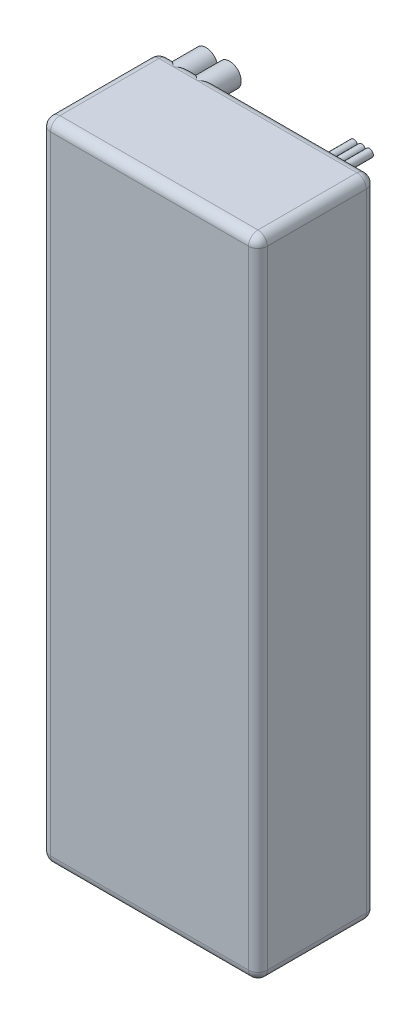
SolidWorks part; units mm, degrees
material "Rubber"
ref_plane "Front" through (0, 0, 0) normal (0, 0, 1) x (1, 0, 0)
ref_plane "Top" through (0, 0, 0) normal (0, 1, 0) x (1, 0, 0)
ref_plane "Right" through (0, 0, 0) normal (1, 0, 0) x (0, 0, -1)
sketch "Sketch1" plane through (0, 0, 0) normal (0, 0, 1) x (1, 0, 0)
  line L1 (-23, 0) -> (23, 0)
  line L2 (-23, 0) -> (-23, 137)
  line L3 (-23, 137) -> (23, 137)
  line L4 (23, 0) -> (23, 137)
  point P4 (0, 0)
  dimension "D1" = 46
  dimension "D2" = 137
extrude "Boss-Extrude1" add sketch "Sketch1" along normal blind 25
fillet "Fillet1" radius 2 12 edges at (0, 0, 0) (0, 137, 0) (-23, 137, 12.5) (-23, 0, 12.5) (-23, 68.5, 0) (23, 0, 12.5) (23, 137, 12.5) (23, 68.5, 0) (0, 137, 25) (23, 68.5, 25) (0, 0, 25) (-23, 68.5, 25)
sketch "Sketch2" plane through (0, 0, 0) normal (0, 0, -1) x (-1, 0, 0)
  line L0 (21, 135) -> (-21, 135) construction
  line L1 (-16.6667, 135) -> (-15, 135) construction
  line L2 (-15, 135) -> (-13.3333, 135) construction
  line L3 (13, 134.55) -> (18, 134.55) construction
  line L4 (-23, 2) -> (-23, 135) construction
  line L5 (-21, 137) -> (21, 137) construction
  line L6 (23, 135) -> (23, 2) construction
  circle A0 centre (-16.6667, 135) radius 0.825
  circle A1 centre (-15, 135) radius 0.825
  circle A2 centre (-13.3333, 135) radius 0.825
  circle A3 centre (13, 134.55) radius 2.45
  circle A4 centre (18, 134.55) radius 2.45
  line M11 (21, 135) -> (-21, 135)
  dimension "D4" = 5
  dimension "D5" = 4.9
  dimension "D6" = 1.65
  dimension "D1" = 3.3333
  dimension "D2" = 8
  dimension "D3" = 5
extrude "Boss-Extrude4" add sketch "Sketch2" along normal blind 5 and the other way up to body separate body contours A0 M11 | A0 M11 | A2 | A1 | A4 | A3
